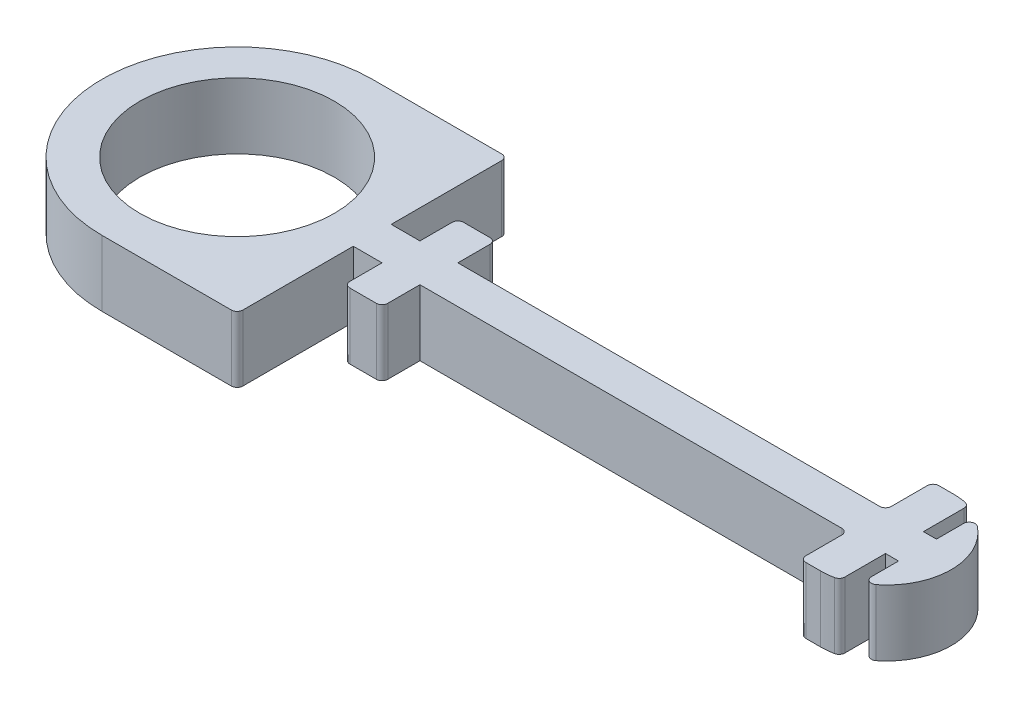
SolidWorks part; units mm, degrees
material "Custom Plastic"
ref_plane "Front Plane" through (0, 0, 0) normal (0, 0, 1) x (1, 0, 0)
ref_plane "Top Plane" through (0, 0, 0) normal (0, 1, 0) x (1, 0, 0)
ref_plane "Right Plane" through (0, 0, 0) normal (1, 0, 0) x (0, 0, -1)
sketch "Sketch1" plane through (0, 0, 0) normal (0, 1, 0) x (1, 0, 0)
  line L0 (0, 0) -> (84.8581, 0) construction
  line L1 (88.8444, -2.475) -> (88.8444, -7.4004)
  line L2 (87.1444, 8.3777) -> (87.1444, 2.475)
  line L3 (82.1944, 8.684) -> (82.1944, 2.475)
  line L4 (84.8581, 8.684) -> (82.1944, 8.684)
  line L5 (87.1444, -2.475) -> (88.8444, -2.475)
  line L6 (87.1444, 2.475) -> (88.8444, 2.475)
  line L7 (88.8444, 2.475) -> (88.8444, 7.4004)
  line L8 (17.65, -17.65) -> (17.65, -2.475)
  line L9 (0, 17.65) -> (17.65, 17.65)
  line L10 (0, -17.65) -> (17.65, -17.65)
  line L11 (21.4, 7.425) -> (21.4, 2.475)
  line L12 (21.4, -7.425) -> (26.35, -7.425)
  line L13 (26.35, -7.425) -> (26.35, -2.475)
  line L14 (21.4, 7.425) -> (26.35, 7.425)
  line L15 (17.65, 2.475) -> (21.4, 2.475)
  line L16 (17.65, -2.475) -> (21.4, -2.475)
  line L17 (17.65, 2.475) -> (17.65, 17.65)
  line L18 (21.4, -2.475) -> (21.4, -7.425)
  line L19 (26.35, 2.475) -> (26.35, 7.425)
  line L20 (84.8581, -8.684) -> (82.1944, -8.684)
  line L21 (26.35, 2.475) -> (82.1944, 2.475)
  line L22 (26.35, -2.475) -> (82.1944, -2.475)
  line L23 (82.1944, -8.684) -> (82.1944, -2.475)
  line L24 (87.1444, -8.3777) -> (87.1444, -2.475)
  circle A0 centre (0, 0) radius 12.7
  arc A1 (0, 17.65) -> (0, -17.65) centre (0, 0) ccw
  arc A2 (87.1444, 8.3777) -> (84.8581, 8.684) centre (84.8581, 0) ccw
  arc A3 (87.1444, -8.3777) -> (84.8581, -8.684) centre (84.8581, 0) cw
  arc A5 (88.8444, -7.4004) -> (88.8444, 7.4004) centre (84.8581, 0) ccw
  point P19 (17.65, 0)
  point P23 (25.9, 0)
  point P24 (20.95, 0)
  dimension "D1" = 25.4
  dimension "D2" = 4.95
  dimension "D5" = 3.75
  dimension "D6" = 2.475
  dimension "D3" = 4.95
  dimension "D4" = 4.95
  dimension "D7" = 1.7
extrude "Boss-Extrude1" add sketch "Sketch1" along normal blind 8.6
fillet "Fillet2" radius 0.75 14 edges at (87.1444, 4.3, 8.3777) (88.8444, 4.3, -7.4004) (88.8444, 4.3, 7.4004) (82.1944, 4.3, 2.475) (82.1944, 4.3, -2.475) (82.1944, 4.3, 8.684) (82.1944, 4.3, -8.684) (87.1444, 4.3, -8.3777) (21.4, 4.3, 7.425) (21.4, 4.3, -7.425) (26.35, 4.3, -7.425) (26.35, 4.3, 7.425) (17.65, 4.3, 17.65) (17.65, 4.3, -17.65)
